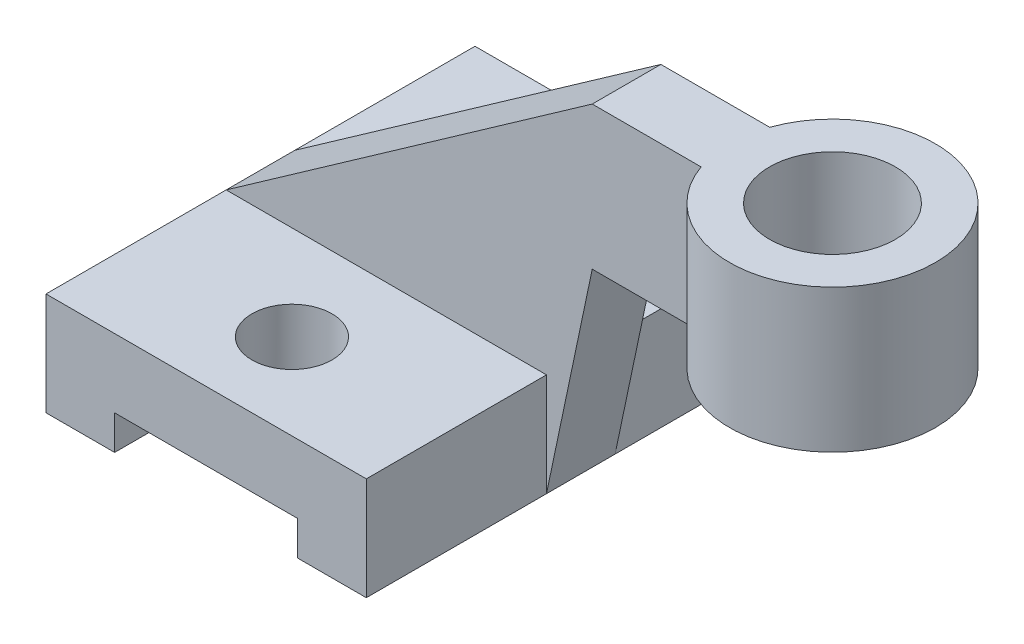
SolidWorks part; units mm, degrees
ref_plane "Front Plane" through (0, 0, 0) normal (0, 0, 1) x (1, 0, 0)
ref_plane "Top Plane" through (0, 0, 0) normal (0, 1, 0) x (1, 0, 0)
ref_plane "Right Plane" through (0, 0, 0) normal (1, 0, 0) x (0, 0, -1)
sketch "Sketch1" plane through (0, 0, 0) normal (0, 0, 1) x (1, 0, 0)
  line L0 (-16, -9) -> (-16, -3)
  line L1 (-28, -9) -> (-16, -9)
  line L2 (-28, -9) -> (-28, 9)
  line L3 (-28, 9) -> (28, 9)
  line L4 (28, -9) -> (28, 9)
  line L5 (-28, -9) -> (28, 9) construction
  line L6 (-28, 9) -> (28, -9) construction
  line L7 (-16, -3) -> (16, -3)
  line L8 (16, -3) -> (16, -9)
  line L9 (16, -9) -> (28, -9)
  line L10 (0, 0) -> (0, 5.1579) construction
  point P0 (0, 0)
  dimension "D1" = 56
  dimension "D2" = 18
  dimension "D3" = 6
  dimension "D4" = 12
extrude "Boss-Extrude1" add sketch "Sketch1" against normal blind 75
ref_plane "Plane4" through (0, 54, 0) normal (0, -1, 0) x (-1, 0, 0)
sketch "Sketch9" plane through (0, 54, 0) normal (0, -1, 0) x (-1, 0, 0)
  line L0 (-55.0294, 43.5) -> (-36, 43.5)
  line L1 (-55.0294, 31.5) -> (-36, 31.5)
  line L2 (-72, 37.5) -> (-37.3466, 37.5) construction
  line L3 (28, 75) -> (28, 0) construction
  line L4 (-36, 43.5) -> (-36, 31.5)
  circle A0 centre (-72, 37.5) radius 11
  arc A1 (-55.0294, 43.5) -> (-55.0294, 31.5) centre (-72, 37.5) ccw
  point P10 (28, 37.5)
  dimension "D1" = 36
  dimension "D2" = 22
  dimension "D5" = 100
  dimension "D3" = 12
  dimension "D4" = 36
extrude "Boss-Extrude3" add sketch "Sketch9" along normal blind 25 separate body
ref_plane "Plane5" through (0, 0, -37.5) normal (0, 0, 1) x (1, 0, 0)
sketch "Sketch11" plane through (0, 0, -37.5) normal (0, 0, 1) x (1, 0, 0)
  line L0 (36, 29) -> (28, -9)
  line L3 (28, -9) -> (28, 9)
  line L5 (28, 9) -> (-28, 9)
  line L6 (-28, 9) -> (36, 54)
  line L9 (36, 54) -> (36, 29)
extrude "Boss-Extrude4" add sketch "Sketch11" along normal mid plane 12 contours L6 L9 L0 L3 L5
sketch "Sketch5" plane through (0, 9, 0) normal (0, 1, 0) x (1, 0, 0)
  line L0 (-28, 75) -> (-28, 43.5) construction
  line L1 (28, 75) -> (-28, 75) construction
  point P0 (0, 15)
  point P2 (0, 60)
  point P10 (0, 0)
  dimension "D1" = 15
  dimension "D2" = 28
  dimension "D3" = 15
hole_wizard "Ø12.0mm Dowel Hole1" positions "Sketch5" profile "Sketch4" hole size "Ø12.0" standard "ISO" end condition up to next
sketch "Sketch4" plane through (0, 9, -15) normal (1, 0, 0) x (0, 0, 1)
  line L0 (0, 0) -> (0, 12)
  line L1 (0, 12) -> (7, 12)
  line L2 (7, 12) -> (7, 0)
  line L5 (7, 0) -> (0, 0)
  line L11 (0, -6.35) -> (0, 107.95) construction
  dimension "Thru Hole Dia." = 14
  dimension "Thru Hole Depth" = 12
